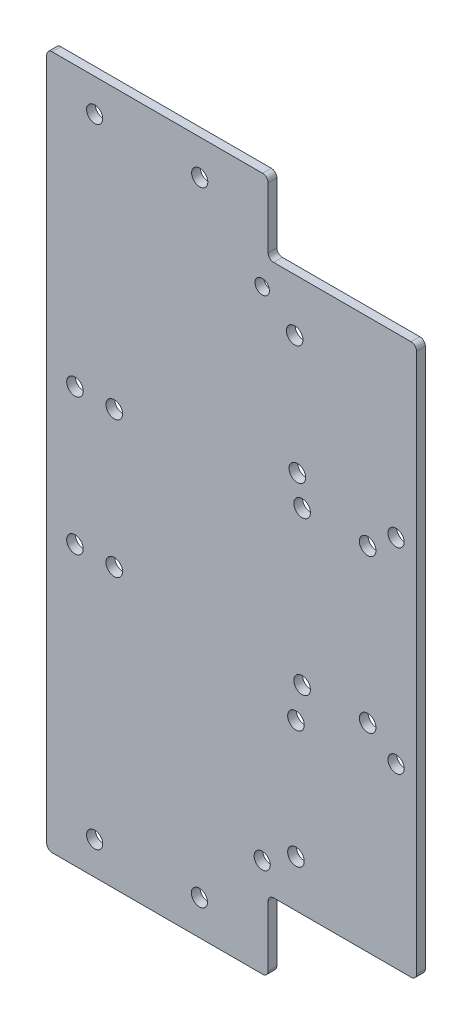
SolidWorks part; units mm, degrees
material "Thornel Mat VMA"
ref_plane "Front Plane" through (0, 0, 0) normal (0, 0, 1) x (1, 0, 0)
ref_plane "Top Plane" through (0, 0, 0) normal (0, 1, 0) x (1, 0, 0)
ref_plane "Right Plane" through (0, 0, 0) normal (1, 0, 0) x (0, 0, -1)
sketch "Sketch2" plane through (0, 0, 0) normal (0, 0, 1) x (-1, 0, 0)
  line L11 (-2.9301, 168.7083) -> (38.7094, 168.7083)
  line L12 (-2.9301, 8.6883) -> (38.7094, 8.6883)
  line L13 (38.7094, -12.1397) -> (38.7094, 8.6883)
  line L14 (143.4971, -12.1397) -> (38.7094, -12.1397)
  line L15 (38.7094, 189.5363) -> (38.7094, 168.7083)
  line L16 (143.4971, 189.5363) -> (38.7094, 189.5363)
  line L17 (104.6174, 110.8598) -> (143.4971, 189.5363)
  line L18 (104.6174, 66.5368) -> (143.4971, -12.1397)
  line L19 (104.6174, 66.5368) -> (72.8674, 66.5368)
  line L20 (72.8674, 66.5368) -> (72.8674, 110.8598)
  line L21 (104.6174, 110.8598) -> (72.8674, 110.8598)
  line L22 (-2.9301, 168.7083) -> (-2.9301, 8.6883)
  line L23 (41.9566, 19.6103) -> (41.9566, 13.2603) construction
  circle A0 centre (41.9566, 160.9613) radius 2.3495
  circle A1 centre (90.6739, 180.0113) radius 2.3495
  circle A2 centre (90.6739, -2.6147) radius 2.3495
  circle A3 centre (3.0351, 117.2098) radius 2.3495
  circle A4 centre (3.0351, 60.1868) radius 2.3495
  circle A5 centre (41.9566, 16.4353) radius 2.0955
  point P36 (41.9566, 16.4353)
  dimension "D3" = 4.699
  dimension "D7" = 31.75
  dimension "D8" = 41.6395
  dimension "D9" = 20.828
  dimension "D10" = 160.02
  dimension "D11" = 20.828
  dimension "D12" = 41.6395
  dimension "D13" = 104.7876
  dimension "D14" = 116.297
  dimension "D15" = 116.297
  dimension "D16" = 44.323
  dimension "D17" = 26.297
  dimension "D18" = 9.525
  dimension "D19" = 28.575
  dimension "D20" = 7.747
  dimension "D21" = 51.9645
  dimension "D22" = 51.4985
  dimension "D23" = 5.9651
  dimension "D24" = 51.4985
  dimension "D25" = 5.9651
  dimension "D26" = 7.747
  dimension "D27" = 3.2471
  dimension "D28" = 9.525
  dimension "D29" = 51.9645
extrude "Boss-Extrude1" add sketch "Sketch2" along normal blind 2.54
sketch "Sketch3" plane through (0, 0, 2.54) normal (0, 0, 1) x (1, 0, 0)
  line L1 (-104.6174, -66.5368) -> (-72.8674, -66.5368)
  line L2 (-104.6174, -66.5368) -> (-104.6174, -110.8598)
  line L3 (-104.6174, -110.8598) -> (-72.8674, -110.8598)
  line L4 (-72.8674, -66.5368) -> (-72.8674, -110.8598)
extrude "Boss-Extrude2" add sketch "Sketch3" against normal up to surface (2.54 mm away) up to face at (-65.9118, -88.6983, 0)
sketch "Sketch4" plane through (0, 0, 2.54) normal (0, 0, 1) x (1, 0, 0)
  line L0 (-104.6174, -66.5368) -> (-104.6174, -66.3082)
  line L1 (-104.6174, -66.5368) -> (-104.6174, -110.8598) construction
  line L2 (-106.6494, -66.4225) -> (2.9301, -66.4225) construction
  line L3 (2.9301, -168.7083) -> (2.9301, -8.6883) construction
  line L4 (-104.6174, -88.6983) -> (2.9301, -88.6983) construction
  line L5 (-106.6494, -110.9741) -> (2.9301, -110.9741) construction
  line L6 (-104.6174, -110.8598) -> (-104.6174, -111.0884)
  circle A0 centre (-96.3957, -68.8355) radius 2.413
  circle A1 centre (-84.9657, -68.8355) radius 2.413
  circle A2 centre (-30.3439, -66.4225) radius 2.413
  circle A3 centre (-11.2939, -66.4225) radius 2.413
  circle A4 centre (-11.2939, -110.9741) radius 2.413
  circle A5 centre (-30.3439, -110.9741) radius 2.413
  circle A6 centre (-84.9657, -108.5611) radius 2.413
  circle A7 centre (-96.3957, -108.5611) radius 2.413
  point P31 (0, 0)
  point P32 (0, 0)
  point P33 (0, 0)
  dimension "D4" = 4.826
  dimension "D5" = 4.826
  dimension "D8" = 4.826
  dimension "D9" = 4.826
  dimension "D10" = 22.2758
  dimension "D3" = 11.43
  dimension "D6" = 19.05
  dimension "D7" = 14.224
extrude "Cut-Extrude1" cut sketch "Sketch4" against normal through all contours A0 | A1 | A2 | A3 | A4 | A5 | A6 | A7
sketch "Sketch5" plane through (0, 0, 2.54) normal (0, 0, 1) x (1, 0, 0)
  circle A0 centre (-31.739, -58.2731) radius 2.413
  dimension "D1" = 4.826
sketch "Sketch6" plane through (0, 0, 2.54) normal (0, 0, 1) x (1, 0, 0)
  circle A0 centre (-32.5114, -23.9918) radius 2.413
  dimension "D1" = 4.826
extrude "Cut-Extrude2" cut sketch "Sketch5" against normal through all
extrude "Cut-Extrude3" cut sketch "Sketch6" against normal through all
sketch "Sketch7" plane through (0, 0, 2.54) normal (0, 0, 1) x (1, 0, 0)
  circle A0 centre (-32.1405, -155.0714) radius 2.413
  circle A1 centre (-32.1405, -120.7814) radius 2.413
  dimension "D1" = 4.826
  dimension "D2" = 4.826
extrude "Cut-Extrude4" cut sketch "Sketch7" against normal through all
sketch "Sketch8" plane through (0, 0, 2.54) normal (0, 0, 1) x (1, 0, 0)
  line L0 (-38.7094, -168.7083) -> (2.9301, -168.7083) construction
  line L1 (-32.2387, 12.4252) -> (-40.2334, 12.4252)
  line L2 (-32.2387, 12.4252) -> (-32.2387, -8.6883)
  line L3 (-32.2387, -8.6883) -> (-40.2334, -8.6883)
  line L4 (-40.2334, 12.4252) -> (-40.2334, -8.6883)
  line L5 (-18.7398, -197.6692) -> (-40.2334, -197.6692)
  line L6 (-18.7398, -197.6692) -> (-18.7398, -168.7083)
  line L7 (-18.7398, -168.7083) -> (-40.2334, -168.7083)
  line L8 (-40.2334, -197.6692) -> (-40.2334, -168.7083)
  line L13 (-38.7094, -189.5363) -> (-38.7094, -168.7083) construction
  line L14 (2.9301, -8.6883) -> (-38.7094, -8.6883) construction
  dimension "D1" = 1.524
extrude "Cut-Extrude5" cut sketch "Sketch8" against normal through all
sketch "Sketch9" plane through (0, 0, 2.54) normal (0, 0, 1) x (1, 0, 0)
  line L0 (-104.6174, -66.5368) -> (-104.6174, 15.6366)
  line L1 (-104.6174, 15.6366) -> (-183.1792, 15.6366)
  line L2 (-104.6174, -66.5368) -> (-104.6174, -202.664)
  line L3 (-104.6174, -202.664) -> (-188.2621, -199.7213)
  line L4 (-188.2621, -199.7213) -> (-183.1792, 15.6366)
extrude "Cut-Extrude6" cut sketch "Sketch9" against normal through all both
extrude "Cut-Extrude7" cut sketch "Sketch10" against normal up to next contours A0
sketch "Sketch10" plane through (-13.5516, -6.8499, 2.54) normal (0, 0, 1) x (-0.9999, 0.0131, 0)
  circle A0 centre (46.6793, -8.1786) radius 2.3495
  circle A1 centre (44.4067, 173.1619) radius 2.3495
fillet "Fillet1" radius 1.5875 8 edges at (-104.6174, -189.5363, 1.27) (-40.2334, -189.5363, 1.27) (-40.2334, -168.7083, 1.27) (2.9301, -168.7083, 1.27) (-40.2334, -8.6883, 1.27) (2.9301, -8.6883, 1.27) (-40.2334, 12.1397, 1.27) (-104.6174, 12.1397, 1.27)
